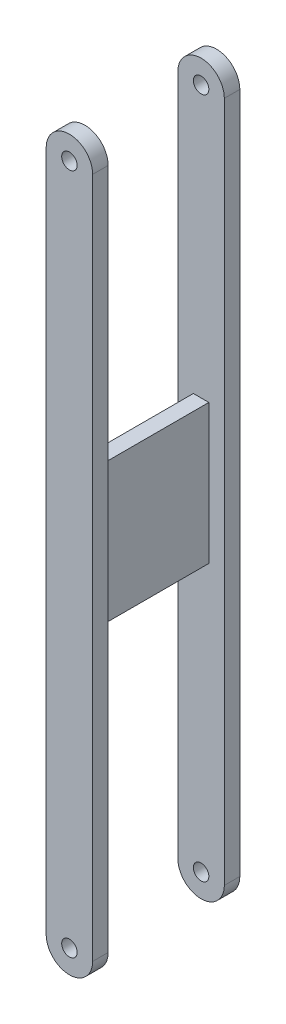
SolidWorks part; units mm, degrees
ref_plane "Plan de face" through (0, 0, 0) normal (0, 0, 1) x (1, 0, 0)
ref_plane "Plan de dessus" through (0, 0, 0) normal (0, 1, 0) x (1, 0, 0)
ref_plane "Plan de droite" through (0, 0, 0) normal (1, 0, 0) x (0, 0, -1)
sketch "Esquisse1" plane through (0, 0, 0) normal (0, 0, 1) x (1, 0, 0)
  line L1 (0, 0) -> (12, 0)
  line L2 (0, 0) -> (0, 188)
  line L3 (0, 188) -> (12, 188)
  line L4 (12, 0) -> (12, 188)
  dimension "D1" = 188
  dimension "D2" = 12
extrude "Boss.-Extru.1" add sketch "Esquisse1" along normal blind 4
sketch "Esquisse2" plane through (0, 0, 4) normal (0, 0, 1) x (1, 0, 0)
  line L0 (12, 0) -> (12, 188) construction
  line L1 (12, 188) -> (0, 188) construction
  line L2 (0, 0) -> (12, 0) construction
  circle A0 centre (6, 182) radius 2
  circle A1 centre (6, 6) radius 2
  dimension "D1" = 4
  dimension "D4" = 4
  dimension "D2" = 6
  dimension "D3" = 6
  dimension "D5" = 6
  dimension "D6" = 6
extrude "Boss.-Extru.2" add sketch "Esquisse2" along normal blind 30
sketch "Esquisse3" plane through (0, 0, 34) normal (0, 0, 1) x (1, 0, 0)
  line L1 (0, 188) -> (12, 188)
  line L2 (0, 188) -> (0, 0)
  line L3 (0, 0) -> (12, 0)
  line L4 (12, 188) -> (12, 0)
  circle A0 centre (6, 182) radius 2 construction
  circle A1 centre (6, 6) radius 2 construction
  dimension "D1" = 6
  dimension "D2" = 6
  dimension "D3" = 6
  dimension "D4" = 6
extrude "Boss.-Extru.3" add sketch "Esquisse3" along normal blind 4
sketch "Esquisse4" plane through (0, 0, 38) normal (0, 0, 1) x (1, 0, 0)
  line L0 (12, 0) -> (12, 188) construction
  line L1 (0, 188) -> (0, 0) construction
  line L2 (12, 188) -> (0, 188) construction
  line L3 (0, 182) -> (0, 193.9471)
  line L4 (0, 193.9471) -> (12, 193.9471)
  line L5 (12, 193.9471) -> (12, 182)
  arc A0 (12, 182) -> (0, 182) centre (6, 182) ccw
  dimension "D3" = 6
  dimension "D1" = 6
  dimension "D2" = 6
extrude "Enlèv. mat.-Extru.1" cut sketch "Esquisse4" against normal blind 74
sketch "Esquisse5" plane through (0, 0, 38) normal (0, 0, 1) x (1, 0, 0)
  line L0 (0, 182) -> (0, 0) construction
  line L1 (12, 0) -> (12, 182) construction
  line L2 (0, 0) -> (12, 0) construction
  line L3 (12, 6) -> (12, -5.889)
  line L4 (12, -5.889) -> (0, -5.889)
  line L5 (0, -5.889) -> (0, 6)
  arc A0 (0, 6) -> (12, 6) centre (6, 6) ccw
  dimension "D1" = 6
  dimension "D2" = 6
  dimension "D3" = 6
extrude "Enlèv. mat.-Extru.2" cut sketch "Esquisse5" against normal blind 74
sketch "Esquisse6" plane through (0, 0, 38) normal (0, 0, 1) x (1, 0, 0)
  circle A0 centre (6, 6) radius 2
  dimension "D1" = 4
extrude "Enlèv. mat.-Extru.3" cut sketch "Esquisse6" against normal blind 74
sketch "Esquisse7" plane through (0, 0, 38) normal (0, 0, 1) x (1, 0, 0)
  circle A0 centre (6, 182) radius 2
  dimension "D1" = 4
sketch "Esquisse8" plane through (0, 0, 4) normal (0, 0, 1) x (1, 0, 0)
  line L0 (0, 182) -> (0, 6) construction
  line L1 (4, 112) -> (8, 112)
  line L2 (4, 112) -> (4, 76)
  line L3 (4, 76) -> (8, 76)
  line L4 (8, 112) -> (8, 76)
  line L5 (12, 6) -> (12, 182) construction
  arc A2 (12, 182) -> (0, 182) centre (6, 182) ccw construction
  arc A3 (0, 6) -> (12, 6) centre (6, 6) ccw construction
  dimension "D4" = 70
  dimension "D1" = 4
  dimension "D2" = 4
  dimension "D3" = 70
extrude "Boss.-Extru.4" add sketch "Esquisse8" along normal blind 30
extrude "Enlèv. mat.-Extru.6" cut sketch "Esquisse7" against normal through all
